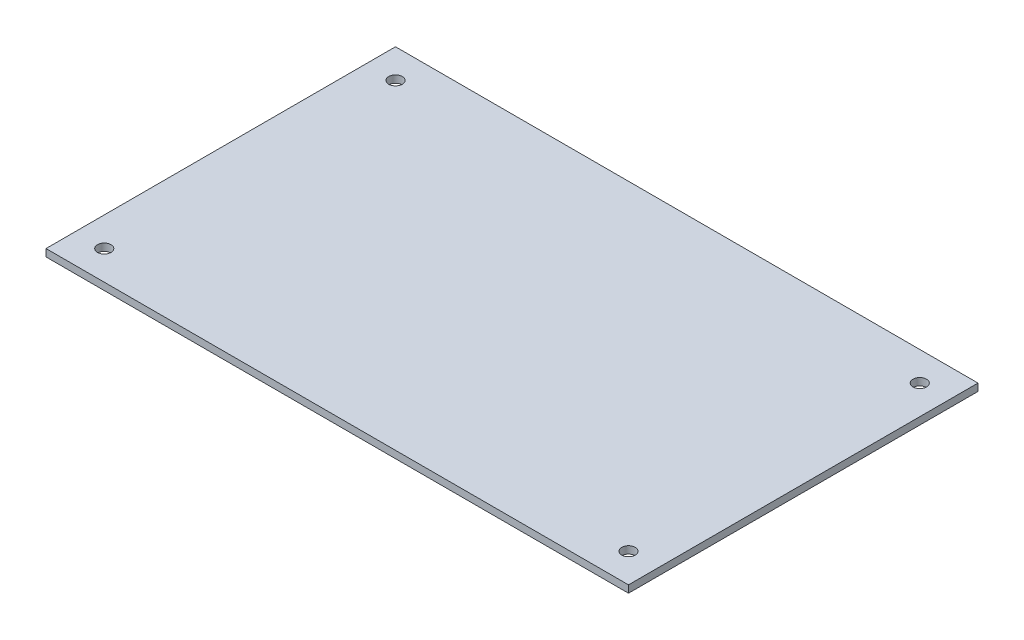
SolidWorks part; units mm, degrees
ref_plane "Front" through (0, 0, 0) normal (0, 0, 1) x (1, 0, 0)
ref_plane "Top" through (0, 0, 0) normal (0, 1, 0) x (1, 0, 0)
ref_plane "Right" through (0, 0, 0) normal (1, 0, 0) x (0, 0, -1)
sketch "Sketch1" plane through (0, 0, 0) normal (0, 1, 0) x (1, 0, 0)
  line L1 (0, 0) -> (101.6, 0)
  line L2 (0, 0) -> (0, 152.4)
  line L3 (0, 152.4) -> (101.6, 152.4)
  line L4 (101.6, 0) -> (101.6, 152.4)
  circle A0 centre (39.37, 144.78) radius 0.381
  circle A1 centre (41.91, 144.78) radius 0.381
  circle A2 centre (44.45, 144.78) radius 0.381
  circle A3 centre (46.99, 144.78) radius 0.381
  circle A4 centre (49.53, 144.78) radius 0.381
  circle A5 centre (52.07, 144.78) radius 0.381
  circle A6 centre (54.61, 144.78) radius 0.381
  circle A7 centre (57.15, 144.78) radius 0.381
  circle A8 centre (59.69, 144.78) radius 0.381
  circle A9 centre (62.23, 144.78) radius 0.381
  dimension "D3" = 39.37
  dimension "D4" = 0.762
  dimension "D5" = 7.62
  dimension "D1" = 152.4
  dimension "D2" = 101.6
  dimension "D6" = 10
sketch "Sketch2" plane through (0, 0, 0) normal (0, 1, 0) x (1, 0, 0)
  line L0 (0, 0) -> (0, 152.4) construction
  line L1 (-12.7, 203.2) -> (114.3, 203.2)
  line L2 (-12.7, 203.2) -> (-12.7, 127)
  line L3 (-12.7, 127) -> (114.3, 127)
  line L4 (114.3, 203.2) -> (114.3, 127)
  dimension "D1" = 76.2
  dimension "D2" = 127
  dimension "D3" = 203.2
  dimension "D4" = 12.7
extrude "Boss-Extrude1" add sketch "Sketch2" along normal blind 1.5875
sketch "Sketch10" plane through (0, 1.5875, 0) normal (0, 1, 0) x (1, 0, 0)
  line L0 (-12.7, 203.2) -> (-12.7, 127) construction
  line L1 (-12.7, 127) -> (114.3, 127) construction
  line L2 (50.8, 203.2) -> (50.8, 127) construction
  line L3 (114.3, 203.2) -> (-12.7, 203.2) construction
  line L4 (114.3, 165.1) -> (-12.7, 165.1) construction
  line L5 (114.3, 127) -> (114.3, 203.2) construction
  point P0 (-6.35, 133.35)
  point P17 (-6.35, 196.85)
  point P19 (107.95, 133.35)
  point P20 (107.95, 196.85)
  dimension "D1" = 6.35
  dimension "D2" = 6.35
hole_wizard "#32 (0.116) Diameter Hole3" positions "Sketch16" profile "Sketch17" hole size "#32" standard "ANSI Inch" end condition through all
sketch "Sketch16" plane through (0, 1.5875, 0) normal (0, 1, 0) x (1, 0, 0)
  point P0 (-6.35, 196.85)
  point P3 (-6.35, 133.35)
  point P6 (107.95, 133.35)
  point P9 (107.95, 196.85)
sketch "Sketch17" plane through (-6.35, 1.5875, -196.85) normal (1, 0, 0) x (0, 0, 1)
  line L0 (0, 0) -> (0, 1.5875)
  line L1 (0, 1.5875) -> (1.4732, 1.5875)
  line L2 (1.4732, 1.5875) -> (1.4732, 0)
  line L5 (1.4732, 0) -> (0, 0)
  line L11 (0, -6.35) -> (0, 107.95) construction
  dimension "Thru Hole Dia." = 2.9464
  dimension "Thru Hole Depth" = 1.5875
